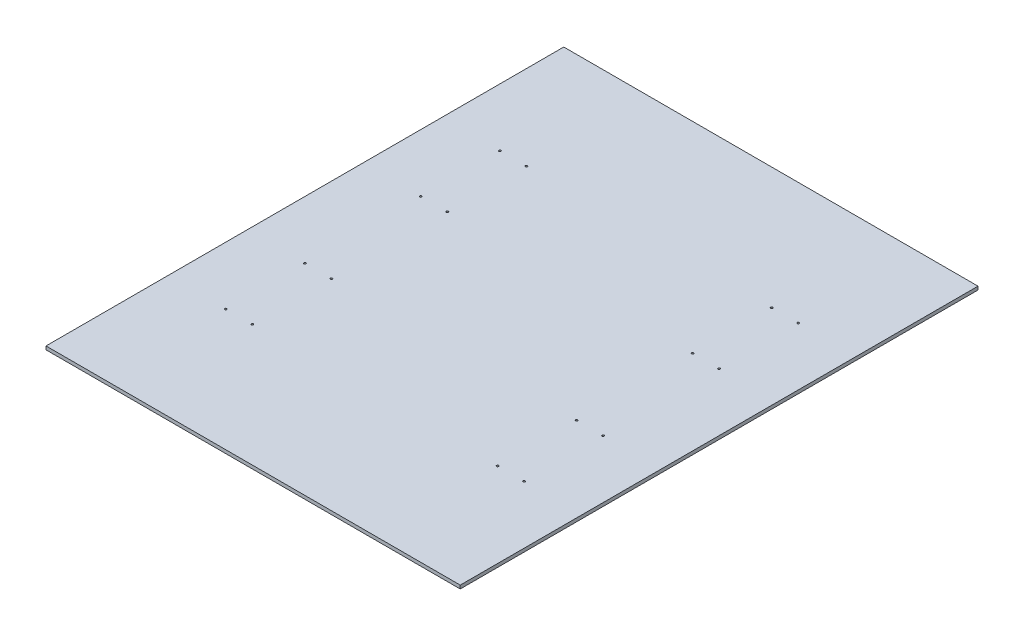
SolidWorks part; units mm, degrees
material "Maple"
ref_plane "Front Plane" through (0, 0, 0) normal (0, 0, 1) x (1, 0, 0)
ref_plane "Top Plane" through (0, 0, 0) normal (0, 1, 0) x (1, 0, 0)
ref_plane "Right Plane" through (0, 0, 0) normal (1, 0, 0) x (0, 0, -1)
sketch "Sketch1" plane through (0, 0, 0) normal (0, 1, 0) x (1, 0, 0)
  line L1 (-609.6, 762) -> (609.6, 762)
  line L2 (-609.6, 762) -> (-609.6, -762)
  line L3 (-609.6, -762) -> (609.6, -762)
  line L4 (609.6, 762) -> (609.6, -762)
  line L5 (-609.6, 762) -> (609.6, -762) construction
  line L6 (-609.6, -762) -> (609.6, 762) construction
  point P0 (0, 0)
  dimension "D1" = 1219.2
  dimension "D2" = 1524
extrude "Boss-Extrude1" add sketch "Sketch1" along normal blind 10
sketch "Sketch2" plane through (0, 10, 0) normal (0, 1, 0) x (1, 0, 0)
  line L0 (-609.6, 762) -> (0, 762) construction
  line L1 (609.6, 762) -> (-609.6, 762) construction
  line L2 (0, 762) -> (0, 287) construction
  line L3 (0, 287) -> (-400, 287) construction
  line L5 (-439, 403.35) -> (-361, 403.35) construction
  line L6 (-439, 403.35) -> (-439, 170.65) construction
  line L7 (-439, 170.65) -> (-361, 170.65) construction
  line L8 (-361, 403.35) -> (-361, 170.65) construction
  line L9 (-439, 403.35) -> (-361, 170.65) construction
  line L10 (-439, 170.65) -> (-361, 403.35) construction
  circle A0 centre (-439, 403.35) radius 3
  circle A1 centre (-361, 403.35) radius 3
  circle A2 centre (-361, 170.65) radius 3
  circle A3 centre (-439, 170.65) radius 3
  dimension "D6" = 6
  dimension "D1" = 609.6
  dimension "D2" = 475
  dimension "D3" = 400
  dimension "D4" = 78
  dimension "D5" = 232.7
extrude "Cut-Extrude1" cut sketch "Sketch2" against normal through all
mirror "Mirror1" about plane through (0, 0, 0) normal (1, 0, 0) of "Cut-Extrude1" second plane through (0, 0, 0) second plane normal (0, 0, 1)
